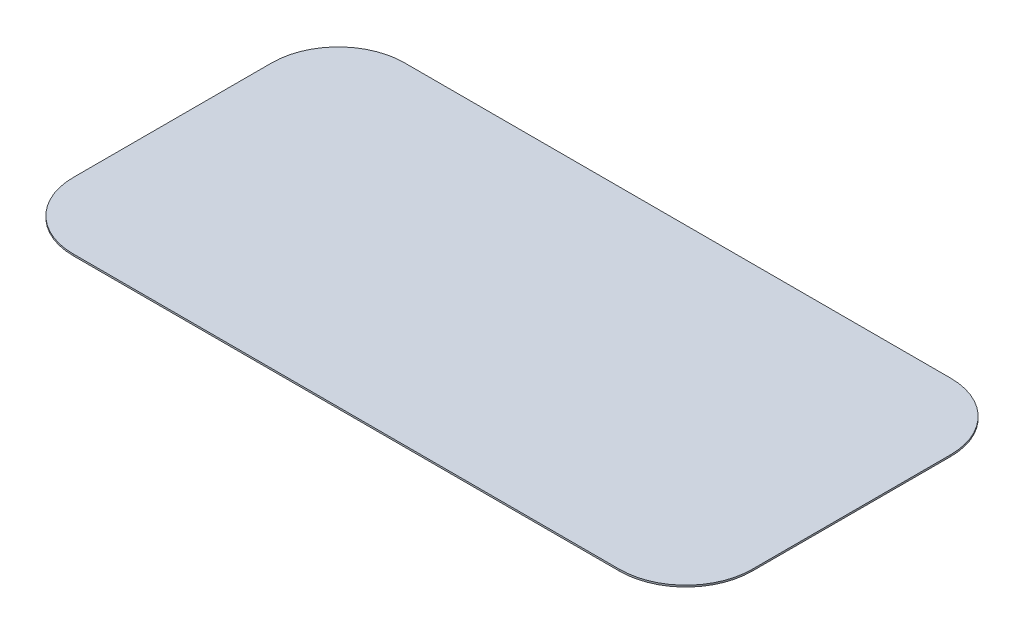
SolidWorks part; units mm, degrees
ref_plane "Front" through (0, 0, 0) normal (0, 0, 1) x (1, 0, 0)
ref_plane "Top" through (0, 0, 0) normal (0, 1, 0) x (1, 0, 0)
ref_plane "Right" through (0, 0, 0) normal (1, 0, 0) x (0, 0, -1)
sketch "Esquisse1" plane through (0, 0, 0) normal (0, 1, 0) x (1, 0, 0)
  line L1 (0, 0) -> (20.5, 0)
  line L2 (0, 0) -> (0, 10)
  line L3 (0, 10) -> (20.5, 10)
  line L4 (20.5, 0) -> (20.5, 10)
  dimension "D1" = 20.5
  dimension "D2" = 10
extrude "Boss.-Extru.1" add sketch "Esquisse1" along normal blind 0.05
fillet "Congé1" radius 2 4 edges at (0, 0.025, -10) (0, 0.025, 0) (20.5, 0.025, 0) (20.5, 0.025, -10)
